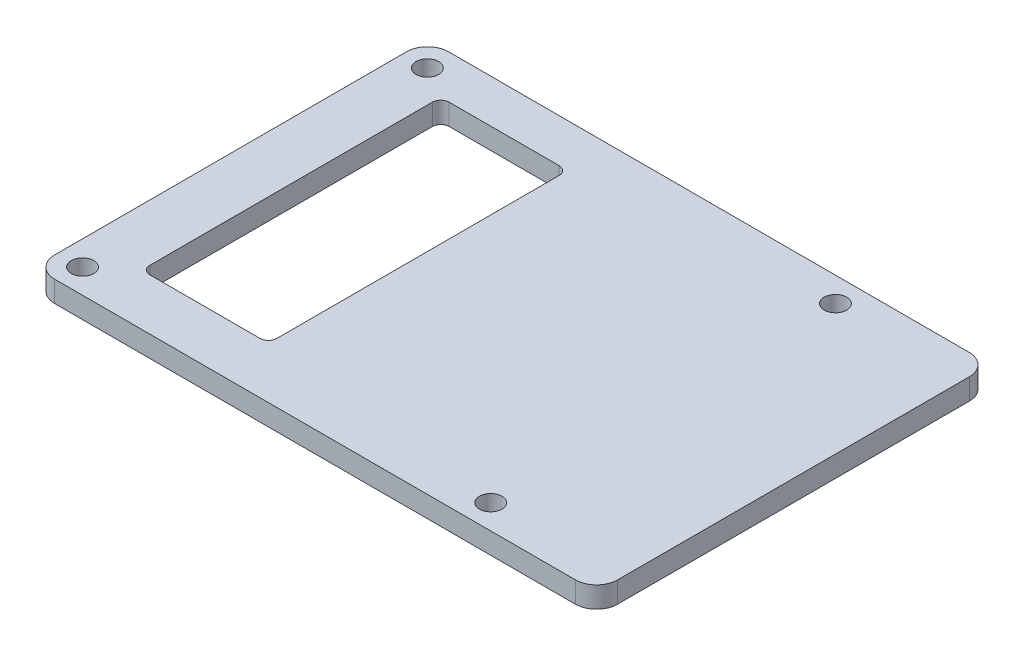
SolidWorks part; units mm, degrees
material "7075-T6 (SN)"
ref_plane "前视基准面" through (0, 0, 0) normal (0, 0, 1) x (1, 0, 0)
ref_plane "上视基准面" through (0, 0, 0) normal (0, 1, 0) x (1, 0, 0)
ref_plane "右视基准面" through (0, 0, 0) normal (1, 0, 0) x (0, 0, -1)
other "Configuration Table"
sketch "草图1" plane through (0, 0, 0) normal (0, 1, 0) x (1, 0, 0)
  line L0 (-70.9525, 18.3001) -> (-70.9986, 18.1669) construction
  line L5 (-80.009, 21.4027) -> (-0.009, 21.4027) construction
  line L6 (-0.009, 21.39) -> (-0.009, -28.5917)
  line L7 (-53.9406, -24.2884) -> (-53.9406, -23.4455) construction
  line L12 (-80.009, 21.4027) -> (-80.009, -28.6044)
  line L13 (-77.0217, -31.5917) -> (12.7873, -31.5917)
  line L14 (15.7746, -28.6044) -> (15.7746, 21.4027)
  line L15 (12.7873, 24.39) -> (-77.0217, 24.39)
  line L16 (-80.009, 21.4027) -> (-80.009, -28.6044)
  line L17 (-77.0217, -31.5917) -> (-3.009, -31.5917)
  line L19 (-3.009, 24.39) -> (-77.0217, 24.39)
  line L20 (-57.0741, 18.2303) -> (-57.0142, 16.884) construction
  line L21 (-57.0142, 16.884) -> (-53.9406, 15.8369) construction
  line L24 (-71.9124, -31.5917) -> (-71.9124, -38.4632) construction
  line L26 (-55.8106, -26.0508) -> (-55.3191, -21.9005) construction
  line L27 (-55.3191, -21.9005) -> (-52.2337, -21.9005) construction
  line L28 (-57.0741, 18.2303) -> (-53.9406, 18.2303) construction
  line L30 (-53.9406, 15.8369) -> (-53.9406, 18.2303) construction
  line L31 (-71.9686, 17.09) -> (-71.9659, 15.0188) construction
  line L32 (-54.4169, -24.2884) -> (-53.9406, -24.2884) construction
  line L33 (-70.9986, 18.1669) -> (-70.8339, 18.1567) construction
  line L34 (-70.8339, 18.1567) -> (-70.8158, 18.2696) construction
  line L35 (-70.8158, 18.2696) -> (-70.9525, 18.3001) construction
  line L36 (-70.8221, 18.2303) -> (-69.2002, 18.2303) construction
  line L38 (-70.7701, 18.2303) -> (-55.1406, 18.2303)
  line L39 (-71.9701, 17.0303) -> (-71.9701, -23.0884)
  line L40 (-70.7701, -24.2884) -> (-55.1406, -24.2884)
  line L41 (-53.9406, 17.0303) -> (-53.9406, -23.0884)
  arc A0 (-70.7701, 18.2303) -> (-71.9701, 17.0303) centre (-70.7701, 17.0303) ccw
  arc A1 (-53.9406, 17.0303) -> (-55.1406, 18.2303) centre (-55.1406, 17.0303) ccw
  arc A2 (-53.9406, -23.0884) -> (-55.1406, -24.2884) centre (-55.1406, -23.0884) cw
  arc A3 (-70.7701, -24.2884) -> (-71.9701, -23.0884) centre (-70.7701, -23.0884) cw
  circle A4 centre (-76.5285, 20.8867) radius 1.6
  circle A5 centre (-18.5286, 20.8866) radius 1.6
  circle A6 centre (-18.5283, -28.1137) radius 1.6
  circle A7 centre (-76.5283, -28.1135) radius 1.6
  arc A8 (-80.009, -28.6044) -> (-77.0217, -31.5917) centre (-77.0217, -28.6044) ccw
  arc A9 (12.7873, -31.5917) -> (15.7746, -28.6044) centre (12.7873, -28.6044) ccw
  arc A10 (15.7746, 21.4027) -> (12.7873, 24.39) centre (12.7873, 21.4027) ccw
  arc A11 (-77.0217, 24.39) -> (-80.009, 21.4027) centre (-77.0217, 21.4027) ccw
  arc A12 (-80.009, -28.6044) -> (-77.0217, -31.5917) centre (-77.0217, -28.6044) ccw
  arc A15 (-77.0217, 24.39) -> (-80.009, 21.4027) centre (-77.0217, 21.4027) ccw
  arc A19 (-0.009, 21.39) -> (-3.009, 24.39) centre (-3.009, 21.39) ccw
  arc A20 (-0.009, -28.5917) -> (-3.009, -31.5917) centre (-3.009, -28.5917) cw
  dimension "D2" = 3.2
  dimension "D3" = 3.2
  dimension "D4" = 3.2
  dimension "D5" = 3.2
  dimension "D6" = 3
  dimension "D7" = 1.2
  dimension "D8" = 1.2
  dimension "D9" = 1.2
  dimension "D10" = 1.2
  dimension "D11" = 3
  dimension "D1" = 0
extrude "凸台-拉伸1" add sketch "草图1" along normal blind 3
sketch "草图3" plane through (0, 0, 0) normal (0, -1, 0) x (1, 0, 0)
  line L0 (-77.0217, 31.5917) -> (-3.009, 31.5917) construction
  line L1 (-15.2271, 31.5917) -> (-3.009, 31.5917)
  line L2 (-15.2271, 31.5917) -> (-15.2271, -24.39)
  line L3 (-15.2271, -24.39) -> (-3.009, -24.39)
  line L11 (-0.009, 28.5917) -> (-0.009, -21.39)
  arc A0 (-0.009, -21.39) -> (-3.009, -24.39) centre (-3.009, -21.39) cw
  arc A1 (-3.009, 31.5917) -> (-0.009, 28.5917) centre (-3.009, 28.5917) cw
  dimension "D1" = 3
  dimension "D2" = 3
